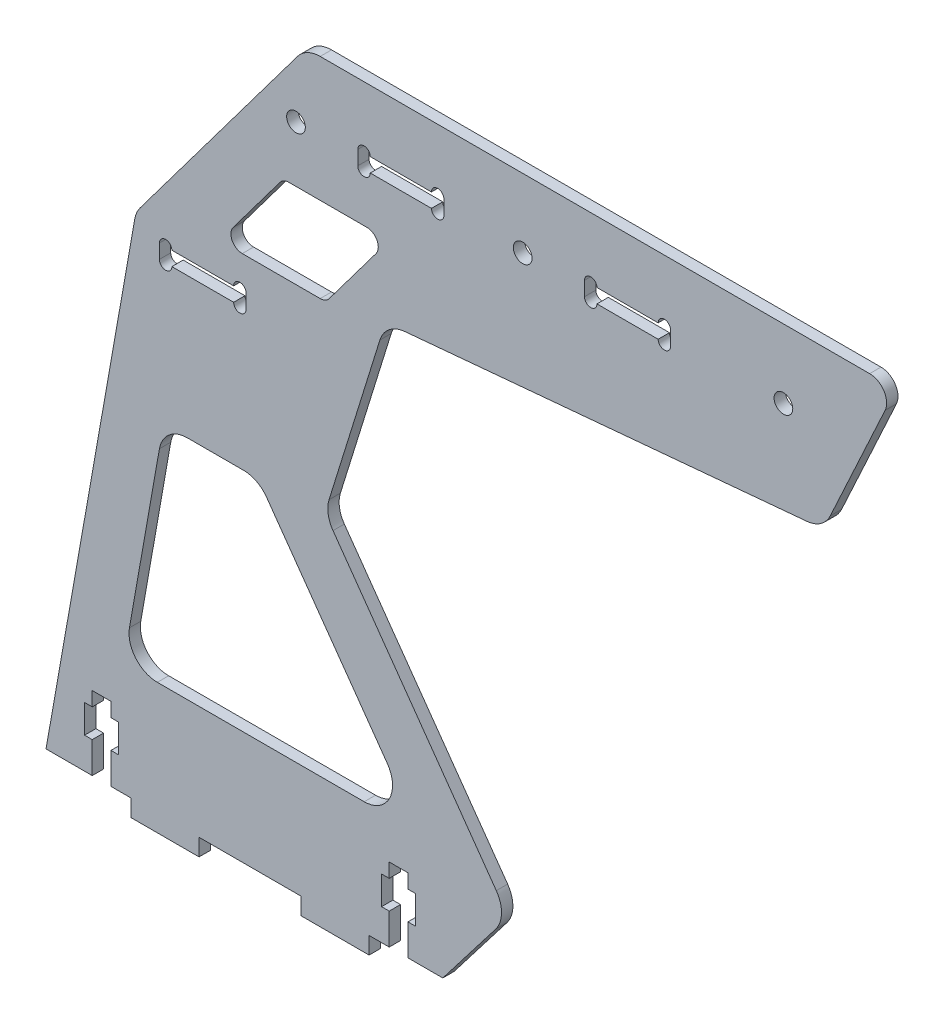
SolidWorks part; units mm, degrees
material "Thornel Mat VMA"
ref_plane "前视基准面" through (0, 0, 0) normal (0, 0, 1) x (1, 0, 0)
ref_plane "上视基准面" through (0, 0, 0) normal (0, 1, 0) x (1, 0, 0)
ref_plane "右视基准面" through (0, 0, 0) normal (1, 0, 0) x (0, 0, -1)
sketch "草图1" plane through (0, 0, 0) normal (0, 0, 1) x (1, 0, 0)
  line L0 (-20, -65) -> (-35, -65)
  line L1 (35, -65) -> (22, -65)
  line L2 (35, -65) -> (35, 65)
  line L3 (35, 65) -> (-35, 65)
  line L4 (-35, -65) -> (-35, 65)
  line L5 (35, -65) -> (-35, 65) construction
  line L6 (35, 65) -> (-35, -65) construction
  line L8 (-20, -65) -> (-20, -68)
  line L9 (-20, -68) -> (-8, -68)
  line L10 (-8, -65) -> (-8, -68)
  line L12 (10, -65) -> (10, -68)
  line L13 (10, -68) -> (22, -68)
  line L14 (22, -65) -> (22, -68)
  line L15 (10, -65) -> (-8, -65)
  point P0 (0, 0)
  dimension "D1" = 70
  dimension "D2" = 3
  dimension "D3" = 12
  dimension "D4" = 3
  dimension "D5" = 12
  dimension "D6" = 30
  dimension "D7" = 15
  dimension "D8" = 130
extrude "凸台-拉伸1" add sketch "草图1" along normal blind 2
sketch "草图2" plane through (0, 0, 2) normal (0, 0, 1) x (1, 0, 0)
  line L0 (-35, -65) -> (-19.1306, 25)
  line L2 (-19.1306, 25) -> (10.8694, 65)
  line L3 (35, 65) -> (-35, 65) construction
  line L4 (10.8694, 65) -> (-35, 65)
  line L5 (-35, 65) -> (-35, -65)
  line L6 (-35, 65) -> (-35, -65) construction
  dimension "D1" = 10
  dimension "D3" = 90
  dimension "D4" = 30
extrude "切除-拉伸1" cut sketch "草图2" against normal blind 2
sketch "草图3" plane through (0, 0, 2) normal (0, 0, 1) x (1, 0, 0)
  line L0 (35, 65) -> (115, 65)
  line L1 (115, 65) -> (85, 0)
  line L2 (85, 0) -> (35, -65)
  line L3 (35, 65) -> (35, -65)
  dimension "D1" = 80
  dimension "D2" = 30
  dimension "D3" = 65
extrude "凸台-拉伸2" add sketch "草图3" against normal up to surface (2 mm away) up to face at (2.6722, -39, 0)
sketch "草图6" plane through (0, 0, 2) normal (0, 0, 1) x (1, 0, 0)
  line L0 (-35, -65) -> (-20, -65) construction
  line L1 (-26.85, -65) -> (-23.55, -65)
  line L2 (-26.85, -65) -> (-26.85, -52)
  line L3 (-26.85, -52) -> (-23.55, -52)
  line L4 (-23.55, -65) -> (-23.55, -52)
  line L5 (-20, -65) -> (-20, -68) construction
  line L6 (22, -65) -> (35, -65) construction
  line L7 (25.55, -65) -> (28.85, -65)
  line L8 (25.55, -65) -> (25.55, -52)
  line L9 (25.55, -52) -> (28.85, -52)
  line L10 (28.85, -65) -> (28.85, -52)
  line L11 (22, -68) -> (22, -65) construction
  dimension "D1" = 13
  dimension "D2" = 3.3
  dimension "D3" = 3.55
  dimension "D4" = 13
  dimension "D5" = 3.3
  dimension "D6" = 3.55
extrude "切除-拉伸3" cut sketch "草图6" against normal blind 2
sketch "草图7" plane through (0, 0, 2) normal (0, 0, 1) x (1, 0, 0)
  line L0 (-23.55, -65) -> (-20, -65) construction
  line L1 (-28.2, -59.5) -> (-22.2, -59.5)
  line L2 (-28.2, -59.5) -> (-28.2, -54.5)
  line L3 (-28.2, -54.5) -> (-22.2, -54.5)
  line L4 (-22.2, -59.5) -> (-22.2, -54.5)
  line L5 (-28.2, -59.5) -> (-22.2, -54.5) construction
  line L6 (-28.2, -54.5) -> (-22.2, -59.5) construction
  line L7 (-23.55, -52) -> (-26.85, -52) construction
  line L8 (28.85, -52) -> (25.55, -52) construction
  line L9 (30.2, -59.5) -> (24.2, -59.5)
  line L10 (30.2, -59.5) -> (30.2, -54.5)
  line L11 (30.2, -54.5) -> (24.2, -54.5)
  line L12 (24.2, -59.5) -> (24.2, -54.5)
  line L13 (30.2, -59.5) -> (24.2, -54.5) construction
  line L14 (30.2, -54.5) -> (24.2, -59.5) construction
  point P0 (-25.2, -57)
  point P10 (-25.2, -52)
  point P11 (27.2, -57)
  point P21 (27.2, -52)
  dimension "D1" = 5
  dimension "D2" = 6
  dimension "D3" = 8
  dimension "D4" = 5
  dimension "D5" = 6
extrude "切除-拉伸4" cut sketch "草图7" against normal blind 2
sketch "草图8" plane through (0, 0, 2) normal (0, 0, 1) x (1, 0, 0)
  line L0 (46.5818, -49.9436) -> (14.2019, -4.3085)
  line L1 (35, -65) -> (85, 0) construction
  line L2 (14.2019, -4.3085) -> (24.8921, 30.1178)
  line L3 (24.8921, 30.1178) -> (102.1527, 37.1643)
  line L4 (85, 0) -> (115, 65) construction
  line L5 (102.1527, 37.1643) -> (85, 0)
  line L6 (85, 0) -> (46.5818, -49.9436)
extrude "切除-拉伸5" cut sketch "草图8" against normal blind 2
sketch "草图9" plane through (0, 0, 2) normal (0, 0, 1) x (1, 0, 0)
  line L0 (-8, -65) -> (10, -65) construction
  line L1 (-12.8, 19.8) -> (-1.9, 19.8)
  line L2 (-15, 19.8) -> (-15, 22.3)
  line L3 (-12.8, 22.3) -> (-1.9, 22.3)
  line L4 (0.3, 19.8) -> (0.3, 22.3)
  arc A0 (0.3, 22.3) -> (-1.9, 22.3) centre (-0.8, 22.3) ccw
  arc A1 (-1.9, 19.8) -> (0.3, 19.8) centre (-0.8, 19.8) ccw
  arc A2 (-12.8, 22.3) -> (-15, 22.3) centre (-13.9, 22.3) ccw
  arc A3 (-15, 19.8) -> (-12.8, 19.8) centre (-13.9, 19.8) ccw
  dimension "D5" = 2.2
  dimension "D6" = 2.2
  dimension "D7" = 2.2
  dimension "D8" = 2.2
  dimension "D1" = 2.5
  dimension "D2" = 15.3
  dimension "D3" = 84.8
  dimension "D4" = 15
extrude "切除-拉伸7" cut sketch "草图9" against normal blind 10
sketch "草图11" plane through (0, 0, 0) normal (0, 0, -1) x (-1, 0, 0)
  line L0 (-2.4311, -5) -> (-30.8126, -45)
  line L1 (-30.8126, -45) -> (21.3192, -45)
  line L2 (21.3192, -45) -> (14.2661, -5)
  line L3 (14.2661, -5) -> (-2.4311, -5)
  line L4 (35, -65) -> (19.1306, 25) construction
  line L5 (-14.2019, -4.3085) -> (-46.5818, -49.9436) construction
  line L6 (8, -65) -> (-10, -65) construction
  dimension "D1" = 10
  dimension "D2" = 10
  dimension "D3" = 20
  dimension "D4" = 5
extrude "切除-拉伸9" cut sketch "草图11" against normal blind 10
fillet "圆角1" radius 5 7 edges at (24.8921, 30.1178, 1) (14.2019, -4.3085, 1) (46.5818, -49.9436, 1) (-21.3192, -45, 1) (30.8126, -45, 1) (-14.2661, -5, 1) (2.4311, -5, 1)
sketch "草图12" plane through (0, 0, 2) normal (0, 0, 1) x (1, 0, 0)
  line L1 (22.2, 54.1) -> (33, 54.1)
  line L2 (20, 54.1) -> (20, 51.6)
  line L3 (22.2, 51.6) -> (33, 51.6)
  line L4 (35.2, 54.1) -> (35.2, 51.6)
  line L5 (-12.8, 19.8) -> (-1.9, 19.8) construction
  line L6 (-15, 22.3) -> (-15, 19.8) construction
  line L7 (62.2, 51.6) -> (73, 51.6)
  line L8 (75.2, 54.1) -> (75.2, 51.6)
  line L9 (62.2, 54.1) -> (73, 54.1)
  line L10 (60, 54.1) -> (60, 51.6)
  arc A0 (22.2, 54.1) -> (20, 54.1) centre (21.1, 54.1) ccw
  arc A1 (20, 51.6) -> (22.2, 51.6) centre (21.1, 51.6) ccw
  arc A2 (35.2, 54.1) -> (33, 54.1) centre (34.1, 54.1) ccw
  arc A3 (33, 51.6) -> (35.2, 51.6) centre (34.1, 51.6) ccw
  arc A4 (73, 51.6) -> (75.2, 51.6) centre (74.1, 51.6) ccw
  arc A5 (75.2, 54.1) -> (73, 54.1) centre (74.1, 54.1) ccw
  arc A6 (62.2, 54.1) -> (60, 54.1) centre (61.1, 54.1) ccw
  arc A7 (60, 51.6) -> (62.2, 51.6) centre (61.1, 51.6) ccw
  dimension "D5" = 2.2
  dimension "D6" = 2.2
  dimension "D7" = 2.2
  dimension "D8" = 2.2
  dimension "D1" = 2.5
  dimension "D2" = 15.2
  dimension "D3" = 31.8
  dimension "D4" = 35
  dimension "D9" = 2
extrude "切除-拉伸10" cut sketch "草图12" against normal blind 50
sketch "草图13" plane through (0, 0, 2) normal (0, 0, 1) x (1, 0, 0)
  line L0 (20, 52.85) -> (75.2, 52.85) construction
  line L1 (20, 54.1) -> (20, 51.6) construction
  line L2 (75.2, 51.6) -> (75.2, 54.1) construction
  circle A0 centre (9.1, 52.85) radius 1.65
  circle A1 centre (49.1, 52.85) radius 1.65
  circle A2 centre (95.1, 52.85) radius 1.65
  arc A3 (20, 51.6) -> (22.2, 51.6) centre (21.1, 51.6) ccw construction
  arc A4 (33, 51.6) -> (35.2, 51.6) centre (34.1, 51.6) ccw construction
  arc A6 (73, 51.6) -> (75.2, 51.6) centre (74.1, 51.6) ccw construction
  dimension "D1" = 3.3
  dimension "D2" = 3.3
  dimension "D3" = 3.3
  dimension "D4" = 12
  dimension "D5" = 15
  dimension "D6" = 21
extrude "切除-拉伸11" cut sketch "草图13" against normal blind 50
fillet "圆角2" radius 5 3 edges at (102.1527, 37.1643, 1) (10.8694, 65, 1) (-19.1306, 25, 1)
sketch "草图15" plane through (0, 0, 2) normal (0, 0, 1) x (1, 0, 0)
  line L0 (6.8694, 43) -> (-4.3806, 28)
  line L1 (-4.3806, 28) -> (14.3694, 28)
  line L2 (14.3694, 28) -> (25.6194, 43)
  line L3 (25.6194, 43) -> (6.8694, 43)
  line L5 (-18.4139, 25.9555) -> (9.3694, 63) construction
  dimension "D1" = 10
  dimension "D2" = 15
  dimension "D3" = 15
  dimension "D4" = 28
extrude "切除-拉伸13" cut sketch "草图15" against normal blind 50
fillet "圆角4" radius 2 4 edges at (-4.3806, 28, 1) (14.3694, 28, 1) (25.6194, 43, 1) (6.8694, 43, 1)
fillet "圆角5" radius 3 1 edges at (115, 65, 1)
